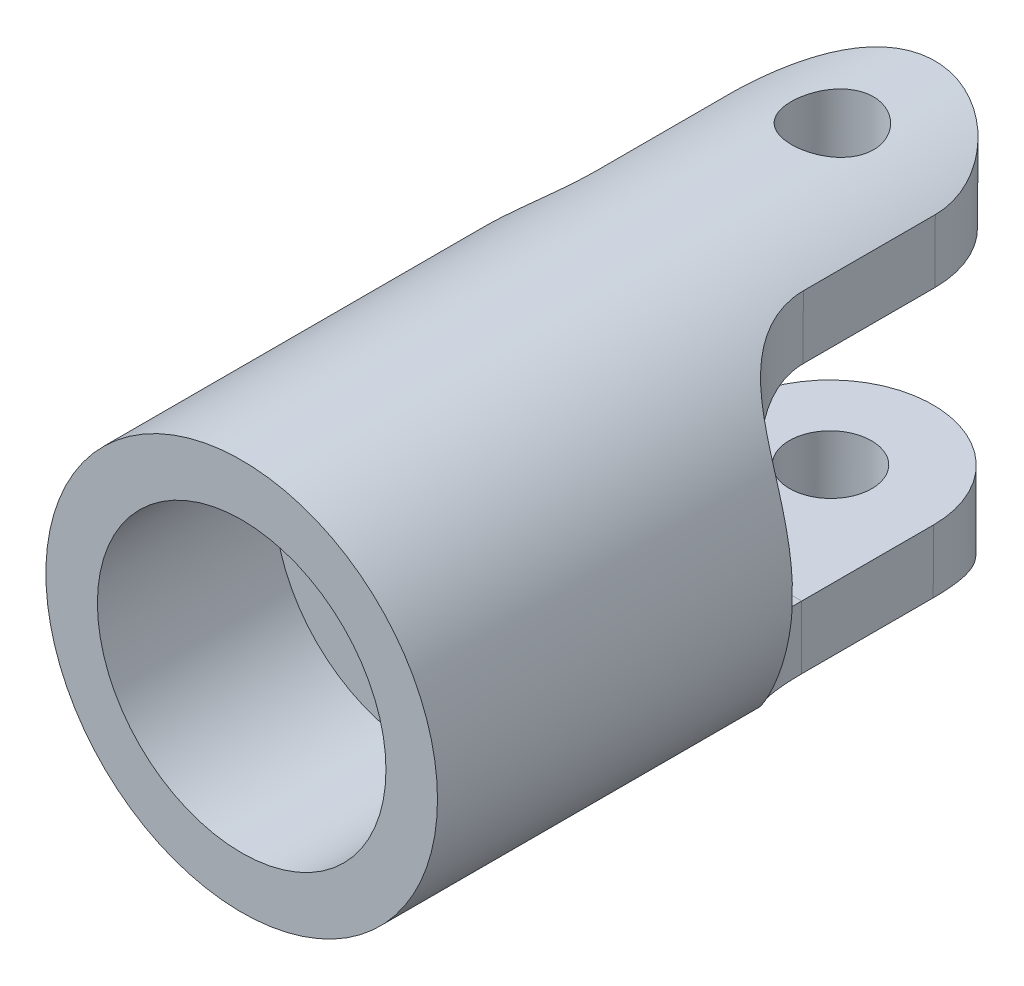
SolidWorks part; units mm, degrees
material "Acier galvanisé"
ref_plane "Plan de face" through (0, 0, 0) normal (0, 0, 1) x (1, 0, 0)
ref_plane "Plan de dessus" through (0, 0, 0) normal (0, 1, 0) x (1, 0, 0)
ref_plane "Plan de droite" through (0, 0, 0) normal (1, 0, 0) x (0, 0, -1)
sketch "Esquisse1" plane through (0, 0, 0) normal (0, 0, 1) x (1, 0, 0)
  circle A0 centre (0, 0) radius 4.75
  dimension "D1" = 9.5
extrude "Boss.-Extru.1" add sketch "Esquisse1" along normal blind 16.8
sketch "Esquisse2" plane through (0, 0, 16.8) normal (0, 0, 1) x (1, 0, 0)
  circle A0 centre (0, 0) radius 3.5
extrude "Enlèv. mat.-Extru.1" cut sketch "Esquisse2" against normal blind 4.3
sketch "Esquisse3" plane through (0, 0, 12.5) normal (0, 0, 1) x (1, 0, 0)
  circle A0 centre (0, 0) radius 2.5
extrude "Enlèv. mat.-Extru.2" cut sketch "Esquisse3" against normal through all
ref_point "Point1"
ref_plane "Plan1" through (-4.7499, 0.0298, 0) normal (-1, 0.0063, 0) x (0, 0, 1)
sketch "Esquisse4" plane through (-4.7499, 0.0298, 0) normal (-1, 0.0063, 0) x (0, 0, 1)
  line L0 (0, 4.75) -> (0, -4.75) construction
  line L1 (0, 2.5) -> (5.7, 2.5)
  line L2 (0, 2.5) -> (0, -2.5)
  line L3 (0, -2.5) -> (5.7, -2.5)
  line L5 (0, -4.75) -> (16.8, -4.75) construction
  arc A0 (5.7, 2.5) -> (5.7, -2.5) centre (5.7, 0) cw
  dimension "D1" = 5.7
  dimension "D2" = 5
  dimension "D3" = 2.25
extrude "Enlèv. mat.-Extru.3" cut sketch "Esquisse4" against normal through all
ref_plane "Plan2" through (-0.0298, -4.7499, 0) normal (-0.0063, -1, 0) x (1, -0.0063, 0)
sketch "Esquisse5" plane through (-0.0298, -4.7499, 0) normal (-0.0063, -1, 0) x (1, -0.0063, 0)
  line L0 (4.75, 8.2) -> (4.75, 16.8) construction
  line L1 (5, 8.2) -> (8.5, 8.2)
  line L2 (-2.5, 5.7) -> (-2.5, 2.5)
  line L4 (2.5, 5.7) -> (2.5, 2.5)
  line L6 (4.75, 16.8) -> (-4.75, 16.8) construction
  line L7 (-6.8689, 8.2) -> (-5, 8.2)
  line L8 (-6.8689, 8.2) -> (-6.8689, -0.8)
  line L9 (-6.8689, -0.8) -> (8.5, -0.8)
  line L10 (8.5, 8.2) -> (8.5, -0.8)
  arc A0 (-2.5, 2.5) -> (2.5, 2.5) centre (0, 2.5) ccw
  arc A1 (-2.5, 5.7) -> (-5, 8.2) centre (-5, 5.7) ccw
  arc A2 (5, 8.2) -> (2.5, 5.7) centre (5, 5.7) ccw
  dimension "D1" = 5
  dimension "D5" = 5
  dimension "D2" = 5
  dimension "D3" = 2.25
  dimension "D4" = 8.6
  dimension "D6" = 6
  dimension "D7" = 9
extrude "Enlèv. mat.-Extru.4" cut sketch "Esquisse5" against normal through all
sketch "Esquisse6" plane through (-0.0298, -4.7499, 0) normal (-0.0063, -1, 0) x (1, -0.0063, 0)
  circle A0 centre (0, 2.5) radius 1
  arc A1 (-2.5, 2.5) -> (2.5, 2.5) centre (0, 2.5) ccw construction
extrude "Enlèv. mat.-Extru.5" cut sketch "Esquisse6" against normal through all
